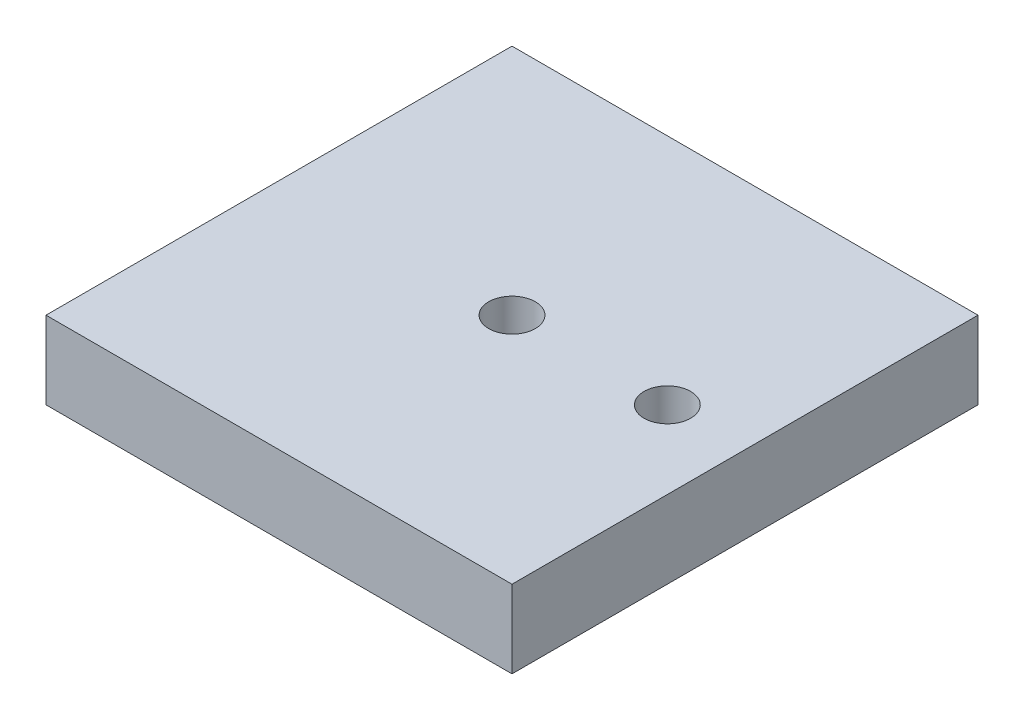
SolidWorks part; units mm, degrees
ref_plane "Front Plane" through (0, 0, 0) normal (0, 0, 1) x (1, 0, 0)
ref_plane "Top Plane" through (0, 0, 0) normal (0, 1, 0) x (1, 0, 0)
ref_plane "Right Plane" through (0, 0, 0) normal (1, 0, 0) x (0, 0, -1)
sketch "Sketch2" plane through (0, 0, 0) normal (0, 1, 0) x (1, 0, 0)
  line L1 (30, 30) -> (-30, 30)
  line L2 (30, 30) -> (30, -30)
  line L3 (30, -30) -> (-30, -30)
  line L4 (-30, 30) -> (-30, -30)
  line L5 (30, 30) -> (-30, -30) construction
  line L6 (30, -30) -> (-30, 30) construction
  point P0 (0, 0)
  dimension "D1" = 60
  dimension "D2" = 60
extrude "Boss-Extrude1" add sketch "Sketch2" along normal blind 10
sketch "Sketch3" plane through (0, 10, 0) normal (0, 1, 0) x (1, 0, 0)
  line L0 (30, -30) -> (30, 30) construction
  circle A0 centre (20, 0) radius 3
  circle A1 centre (0, 0) radius 3
  dimension "D1" = 6
  dimension "D2" = 6
  dimension "D3" = 10
  dimension "D4" = 20
extrude "Cut-Extrude1" cut sketch "Sketch3" against normal through all
